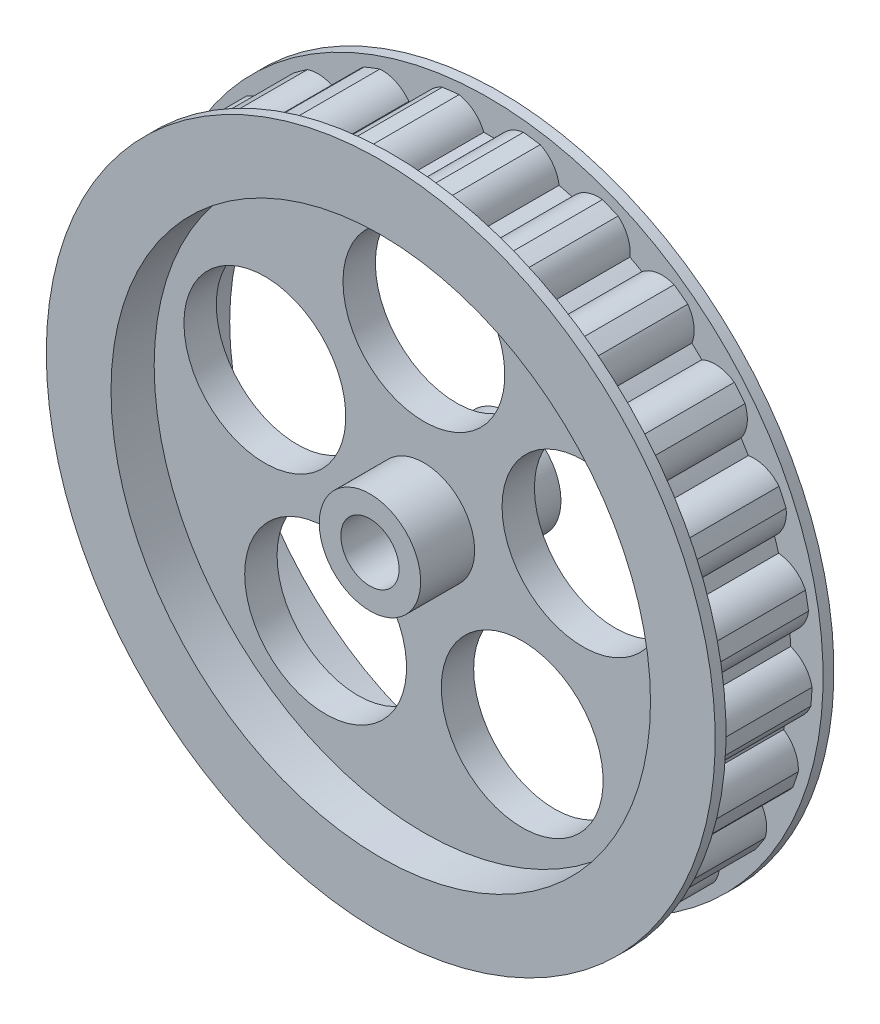
SolidWorks part; units mm, degrees
ref_plane "Front Plane" through (0, 0, 0) normal (0, 0, 1) x (1, 0, 0)
ref_plane "Top Plane" through (0, 0, 0) normal (0, 1, 0) x (1, 0, 0)
ref_plane "Right Plane" through (0, 0, 0) normal (1, 0, 0) x (0, 0, -1)
sketch "Sketch1" plane through (0, 0, 0) normal (1, 0, 0) x (0, 0, -1)
  line L0 (-3.0542, 0) -> (3.0542, 0)
  line L1 (-1.5, 2.7) -> (1.5, 2.7)
  line L2 (1.5, 2.7) -> (1.5, 25)
  line L3 (1.5, 25) -> (4.5, 25)
  line L4 (4.5, 25) -> (4.5, 30)
  line L5 (4.5, 30) -> (-4.5, 30)
  line L6 (-4.5, 30) -> (-4.5, 25)
  line L7 (-4.5, 25) -> (-1.5, 25)
  line L8 (-1.5, 25) -> (-1.5, 2.7)
  point P4 (0, 0)
  point P8 (0, 2.7)
  dimension "D1" = 3
  dimension "D2" = 30
  dimension "D3" = 2.7
  dimension "D4" = 9
  dimension "D5" = 3
  dimension "D6" = 1.5
  dimension "D7" = 5
revolve "Revolve1" add sketch "Sketch1" angle 360 about L0
sketch "Sketch2" plane through (0, 0, -4.5) normal (0, 0, -1) x (-1, 0, 0)
  circle A3 centre (0, 0) radius 30 construction
  arc A4 (0.45, 27.9964) -> (-0.8174, 27.9881) centre (0, 0) ccw
  arc A5 (2.7378, 29.8748) -> (-3.2221, 29.8265) centre (0, 0) ccw
  arc A6 (-3.2221, 29.8265) -> (-0.8174, 27.9881) centre (-3.5929, 26.8495) cw
  arc A7 (0.45, 27.9964) -> (2.7378, 29.8748) centre (3.3068, 26.8495) cw
  circle A8 centre (0, 0) radius 25 construction
  dimension "D1" = 3
  dimension "D2" = 3
extrude "Cut-Extrude1" cut sketch "Sketch2" against normal through all
pattern_circular "CirPattern1" count 25 over 360 about axis through (0, 0, 0) along (0, 0, 1) of "Cut-Extrude1"
sketch "Sketch3" plane through (0, 0, -1.5) normal (0, 0, -1) x (-1, 0, 0)
  circle A0 centre (0, 15.5) radius 7.5
  dimension "D1" = 15
  dimension "D2" = 15.5
  dimension "D3" = 0
extrude "Cut-Extrude2" cut sketch "Sketch3" against normal through all
pattern_circular "CirPattern2" count 5 over 360 about axis through (0, 0, 0) along (0, 0, 1) of "Cut-Extrude2"
sketch "Sketch4" plane through (0, 0, -4.5) normal (0, 0, -1) x (-1, 0, 0)
  circle A0 centre (0, 0) radius 31
  circle A1 centre (0, 0) radius 25
  circle A2 centre (0, 0) radius 25 construction
  arc A3 (29.5653, 5.0886) -> (29.2587, 6.628) centre (0, 0) ccw construction
  dimension "D1" = 0
  dimension "D2" = 0
  dimension "D3" = 1
extrude "Boss-Extrude1" add sketch "Sketch4" along normal blind 1
sketch "Sketch5" plane through (0, 0, -1.5) normal (0, 0, -1) x (-1, 0, 0)
  circle A0 centre (0, 0) radius 2.7
  circle A1 centre (0, 0) radius 4.7
  circle A2 centre (0, 0) radius 2.7 construction
  dimension "D1" = 0
  dimension "D2" = 2
extrude "Boss-Extrude2" add sketch "Sketch5" along normal blind 5
mirror "Mirror2" about plane through (0, 0, 0) normal (0, 0, 1) of "Boss-Extrude2"
mirror "Mirror3" about plane through (0, 0, 0) normal (0, 0, 1) of "Boss-Extrude1"
